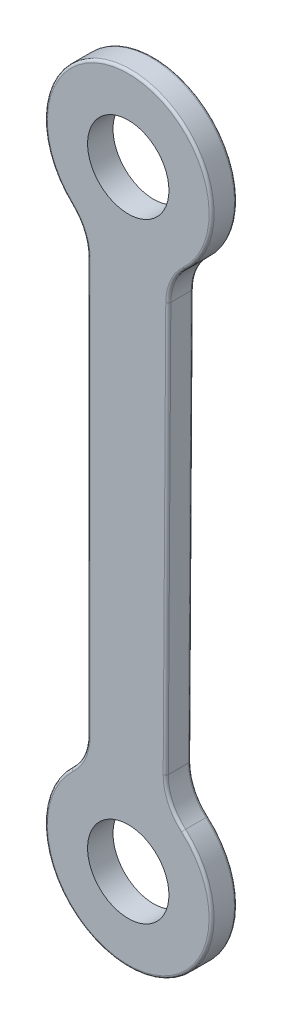
SolidWorks part; units mm, degrees
ref_plane "前视基准面" through (0, 0, 0) normal (0, 0, 1) x (1, 0, 0)
ref_plane "上视基准面" through (0, 0, 0) normal (0, 1, 0) x (1, 0, 0)
ref_plane "右视基准面" through (0, 0, 0) normal (1, 0, 0) x (0, 0, -1)
other "Configuration Table"
sketch "草图1" plane through (0, 0, 0) normal (0, 0, 1) x (1, 0, 0)
  line L0 (0, 0) -> (0, 8) construction
  line L1 (-8, 19.3055) -> (-8, 100.6945)
  line L2 (7.3656, 19.9417) -> (7.8774, 100.6442)
  line L3 (0, 112) -> (0, 120) construction
  circle A2 centre (0, 120) radius 8
  circle A3 centre (0, 0) radius 8
  arc A4 (11.1043, 107.9379) -> (-11.1806, 108.0085) centre (0, 120) ccw
  arc A5 (-11.1806, 11.9915) -> (10.7864, 12.3472) centre (0, 0) ccw
  arc A6 (-8, 100.6945) -> (-11.1806, 108.0085) centre (-18, 100.6945) ccw
  arc A7 (7.3656, 19.9417) -> (10.7864, 12.3472) centre (17.3654, 19.8783) ccw
  arc A8 (-8, 19.3055) -> (-11.1806, 11.9915) centre (-18, 19.3055) cw
  arc A9 (7.8774, 100.6442) -> (11.1043, 107.9379) centre (17.8772, 100.5807) cw
  point P3 (0, 60)
  point P7 (-14.3108, 112)
  point P15 (14.3108, 112)
  point P16 (-14.3108, 8)
  point P17 (14.3108, 8)
  dimension "D2" = 8
  dimension "D3" = 8
  dimension "D4" = 10
  dimension "D5" = 10
  dimension "D1" = 120
extrude "凸台-拉伸1" add sketch "草图1" along normal blind 5
fillet "圆角1" radius 0.5 16 edges at (8.2476, 15.7714, 0) (0.2655, -16.393, 0) (-8.8295, 15.3177, 0) (-8, 60, 0) (-8.8295, 104.6823, 0) (0.052, 136.395, 0) (8.7322, 104.6266, 0) (7.6215, 60.2929, 5) (8.2476, 15.7714, 5) (0.2655, -16.393, 5) (-8.8295, 15.3177, 5) (-8, 60, 5) (-8.8295, 104.6823, 5) (7.6215, 60.2929, 0) (8.7322, 104.6266, 5) (0.052, 136.395, 5)
